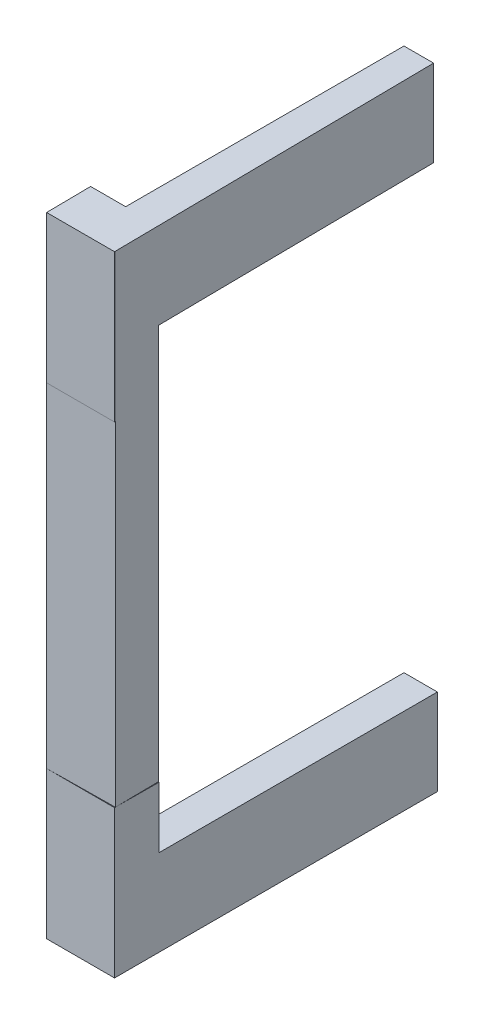
SolidWorks part; units mm, degrees
ref_plane "Front Plane" through (0, 0, 0) normal (0, 0, 1) x (1, 0, 0)
ref_plane "Top Plane" through (0, 0, 0) normal (0, 1, 0) x (1, 0, 0)
ref_plane "Right Plane" through (0, 0, 0) normal (1, 0, 0) x (0, 0, -1)
sketch "Sketch1" plane through (0, 0, 0) normal (0, 1, 0) x (1, 0, 0)
  line L0 (-12.8, -12.8) -> (-13.1, 12.8)
  line L1 (-12.8, 12.8) -> (12.8, 12.8) construction
  line L2 (-12.8, 12.8) -> (-12.8, -12.8) construction
  line L4 (12.8, 12.8) -> (12.8, -12.6) construction
  line L5 (-13.1, 12.8) -> (13.1, 12.8)
  line L6 (13.1, 12.8) -> (12.8, -12.6)
  line L7 (-16.7997, -12.8469) -> (-17.1471, 16.8)
  line L8 (-17.1471, 16.8) -> (17.1475, 16.8)
  line L9 (17.1475, 16.8) -> (16.7997, -12.6472)
  line L11 (-16.7997, -12.8469) -> (-12.8, -12.8)
  line L12 (12.8, -12.6) -> (16.7997, -12.6472)
  dimension "D1" = 25.6
  dimension "D2" = 25.4
  dimension "D3" = 0.3
  dimension "D4" = 0.3
  dimension "D5" = 4
extrude "Boss-Extrude1" add sketch "Sketch1" along normal blind 30
sketch "Sketch2" plane through (0, 30, 0) normal (0, 1, 0) x (1, 0, 0)
  line L0 (0.0002, 16.8) -> (0.0002, 30.8112) construction
  line L1 (17.1475, 16.8) -> (-17.1471, 16.8) construction
  line L2 (0.0002, 36.8) -> (-4.0998, 36.8) construction
  line L3 (0.0002, 36.8) -> (2.1002, 36.8) construction
  line L4 (-4.0998, 36.8) -> (-4.0998, 23.7851)
  line L5 (-2.0998, 36.8) -> (-2.0998, 23.7851)
  line L6 (-11.0849, 16.8) -> (-5.4334, 16.8)
  line L7 (-4.0998, 36.8) -> (-2.0998, 36.8)
  line L8 (4.1002, 36.8) -> (2.1002, 36.8)
  line L9 (11.0853, 16.8) -> (5.4337, 16.8)
  line L10 (2.1002, 36.8) -> (2.1002, 23.7851)
  line L11 (4.1002, 36.8) -> (4.1002, 23.7851)
  arc A0 (-4.0998, 23.7851) -> (-11.0849, 16.8) centre (-11.0849, 23.7851) cw
  arc A1 (-2.0998, 23.7851) -> (-5.4334, 16.8) centre (-11.0849, 23.7851) cw
  arc A2 (-2.0998, 23.7851) -> (-11.0849, 14.8) centre (-11.0849, 23.7851) cw construction
  arc A3 (4.1002, 23.7851) -> (11.0853, 16.8) centre (11.0853, 23.7851) ccw
  arc A4 (2.1002, 23.7851) -> (5.4337, 16.8) centre (11.0853, 23.7851) ccw
  dimension "D1" = 20
  dimension "D2" = 4.1
  dimension "D3" = 2
sketch "Sketch3" plane through (16.9467, 0, 0.2002) normal (0.9999, 0, 0.0118) x (0.0118, 0, -0.9999)
  line L0 (-12.448, 0) -> (10.952, 0) construction
  line L1 (-0.748, 0) -> (-0.748, 30) construction
  line L5 (-12.448, 30) -> (17.0013, 30) construction
  circle A0 centre (-0.748, 15) radius 4
  dimension "D1" = 11.7
extrude "Cut-Extrude1" cut sketch "Sketch3" against normal blind 40
sketch "Sketch4" plane through (0, 0, -16.8) normal (0, 0, -1) x (-1, 0, 0)
  line L0 (17.1471, 0) -> (-17.1475, 30) construction
  line L1 (-0.0002, 15) -> (10.9998, 15) construction
  line L2 (10.9998, -5.5) -> (10.9998, 35.5)
  line L3 (10.9998, 35.5) -> (13.9998, 35.5)
  line L4 (10.9998, -5.5) -> (13.9998, -5.5)
  line L6 (13.9998, 35.5) -> (13.9998, -5.5)
  point P8 (10.9998, 15)
  point P9 (0, 0)
  dimension "D1" = 3
extrude "Boss-Extrude2" add sketch "Sketch4" against normal blind 4
sketch "Sketch5" plane through (0, 0, -16.8) normal (0, 0, -1) x (-1, 0, 0)
  line L1 (13.9998, 35.5) -> (13.9998, 43.25)
  line L11 (10.9998, 35.5) -> (10.9998, 43.25)
  line L17 (10.9998, 35.5) -> (13.9998, 35.5)
  line L18 (10.9998, 43.25) -> (13.9998, 43.25)
  line L21 (17.1471, 15) -> (-23.8791, 15) construction
  line L22 (17.1471, 30) -> (17.1471, 0) construction
  line L23 (10.9998, -13.25) -> (13.9998, -13.25)
  line L24 (10.9998, -5.5) -> (13.9998, -5.5)
  line L25 (10.9998, -5.5) -> (10.9998, -13.25)
  line L26 (13.9998, -5.5) -> (13.9998, -13.25)
extrude "Boss-Extrude3" add sketch "Sketch5" against normal blind 4 and the other way blind 25
sketch "Sketch6" plane through (-13.9998, 0, 0) normal (-1, 0, 0) x (0, 0, 1)
  line L0 (-16.8, 43.25) -> (-16.8, -13.25)
  line L1 (-41.8, 43.25) -> (-12.8, 43.25) construction
  line L2 (-12.8, -13.25) -> (-12.8, 43.25)
  line L3 (-12.8, -13.25) -> (-16.8, -13.25)
  line L4 (-12.8, 43.25) -> (-16.8, 43.25)
extrude "Boss-Extrude4" add sketch "Sketch6" along normal up to surface (3.1005 mm away)
sketch "Sketch7" plane through (-16.9479, 0, 0.1986) normal (-0.9999, 0, 0.0117) x (0.0117, 0, 0.9999)
  line L0 (15.8117, 30) -> (-12.9995, 30)
  line L1 (-12.9995, 30) -> (-12.9995, 0)
  line L2 (-12.9995, 0) -> (19.0119, 0)
  line L3 (15.8117, 30) -> (19.0119, 0)
  point P8 (12.6491, 30)
  point P9 (15.8117, 30)
extrude "Cut-Extrude3" cut sketch "Sketch7" against normal blind 47
sketch "Sketch8" plane through (-0.1523, 0, -12.9986) normal (0.0117, 0, 0.9999) x (0.9999, 0, -0.0117)
  line L0 (-10.8482, 0) -> (-10.8482, 46.5089)
  line L1 (-10.8482, 46.5089) -> (34.8914, 42.7824)
  line L2 (34.8914, 42.7824) -> (32.9595, 0)
  line L3 (32.9595, 0) -> (23.9671, -10.6265)
  line L4 (23.9671, -10.6265) -> (-10.8482, 0)
extrude "Cut-Extrude4" cut sketch "Sketch8" against normal blind 47
